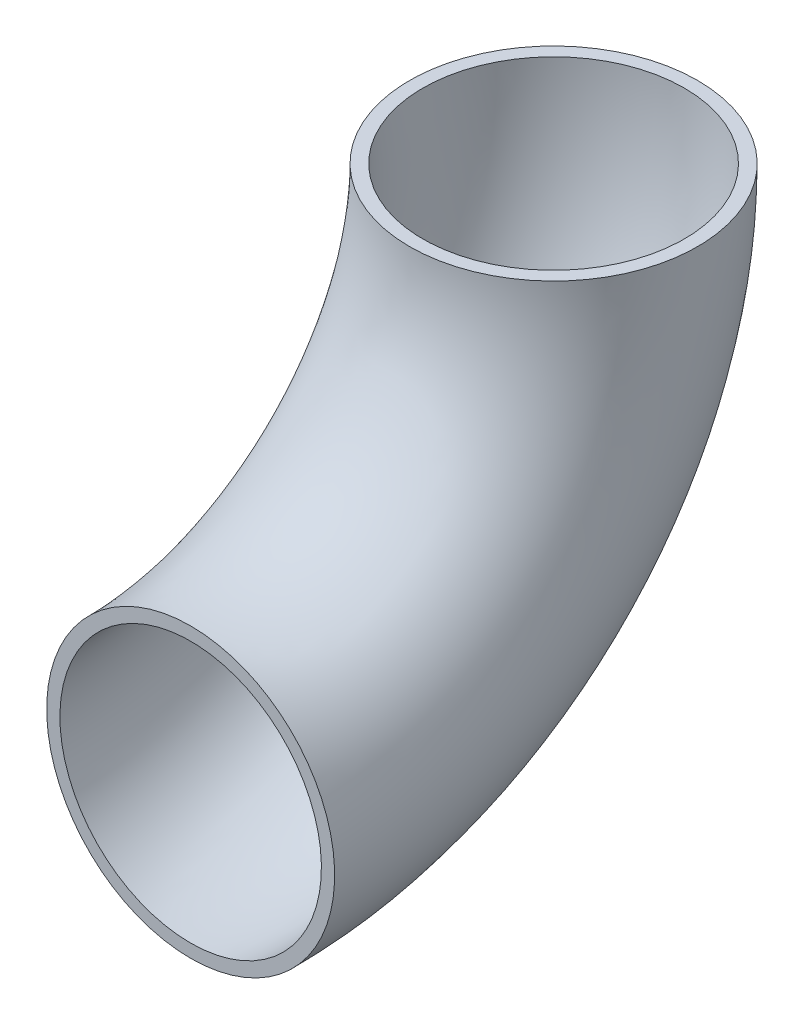
SolidWorks part; units mm, degrees
material "AISI 304"
ref_plane "Ön Düzlem" through (0, 0, 0) normal (0, 0, 1) x (1, 0, 0)
ref_plane "Üst Düzlem" through (0, 0, 0) normal (0, 1, 0) x (1, 0, 0)
ref_plane "Sağ Düzlem" through (0, 0, 0) normal (1, 0, 0) x (0, 0, -1)
sketch "Çizim1" plane through (0, 0, 0) normal (1, 0, 0) x (0, 0, -1)
  line L0 (0, 0) -> (0, 76) construction
  line L1 (0, 76) -> (76, 76) construction
  arc A0 (0, 0) -> (76, 76) centre (0, 76) ccw
  dimension "D1" = 76
sketch "Çizim2" plane through (0, 0, 0) normal (0, 0, 1) x (1, 0, 0)
  circle A0 centre (0, 0) radius 30.15
  circle A1 centre (0, 0) radius 27.38
  dimension "D1" = 60.3
  dimension "D2" = 2.77
sweep "Süpür1" add profiles "Çizim2" path "Çizim1"
